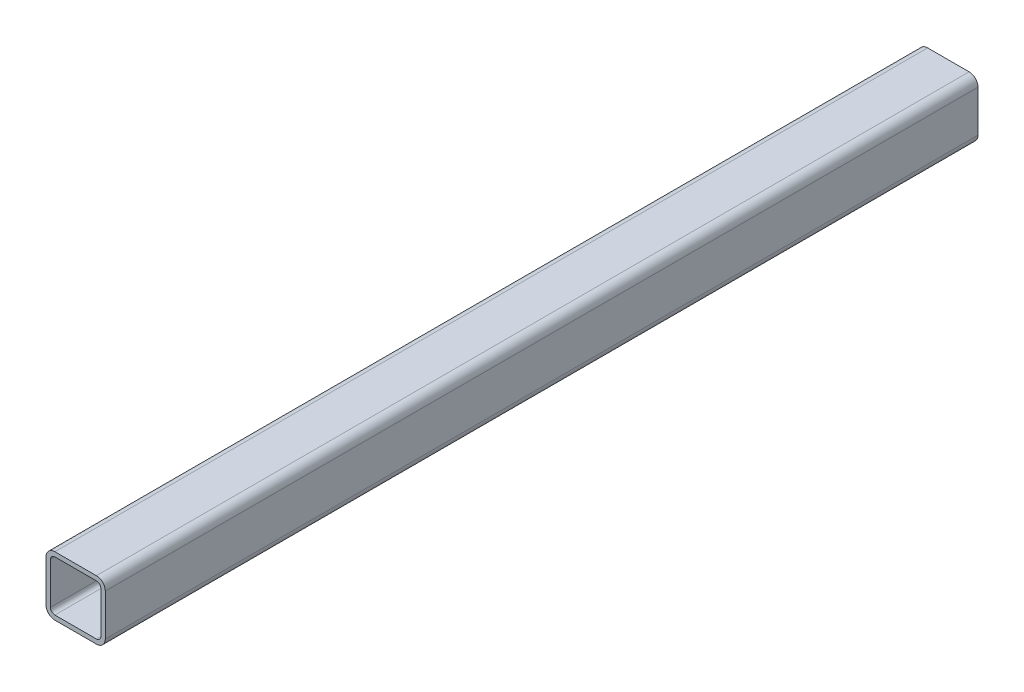
SolidWorks part; units mm, degrees
material "AISI 304"
ref_plane "Front Plane" through (0, 0, 0) normal (0, 0, 1) x (1, 0, 0)
ref_plane "Top Plane" through (0, 0, 0) normal (0, 1, 0) x (1, 0, 0)
ref_plane "Right Plane" through (0, 0, 0) normal (1, 0, 0) x (0, 0, -1)
sketch "Эскиз1" plane through (0, 0, 0) normal (0, 0, 1) x (1, 0, 0)
  line L0 (-14, 17) -> (14, 17)
  line L1 (-14, 20) -> (14, 20)
  line L2 (-20, 14) -> (-20, -14)
  line L3 (-14, -20) -> (14, -20)
  line L4 (20, 14) -> (20, -14)
  line L5 (-20, 20) -> (20, -20) construction
  line L6 (-20, -20) -> (20, 20) construction
  line L7 (17, 14) -> (17, -14)
  line L8 (-14, -17) -> (14, -17)
  line L9 (-17, 14) -> (-17, -14)
  arc A0 (14, 20) -> (20, 14) centre (14, 14) cw
  arc A1 (14, -20) -> (20, -14) centre (14, -14) ccw
  arc A2 (-20, -14) -> (-14, -20) centre (-14, -14) ccw
  arc A3 (-14, 20) -> (-20, 14) centre (-14, 14) ccw
  arc A4 (14, 17) -> (17, 14) centre (14, 14) cw
  arc A5 (14, -17) -> (17, -14) centre (14, -14) ccw
  arc A6 (-17, -14) -> (-14, -17) centre (-14, -14) ccw
  arc A7 (-14, 17) -> (-17, 14) centre (-14, 14) ccw
  point P0 (0, 0)
  dimension "D1" = 6
  dimension "D2" = 40
  dimension "D3" = 40
  dimension "D4" = 3
extrude "Бобышка-Вытянуть1" add sketch "Эскиз1" along normal mid plane 589
